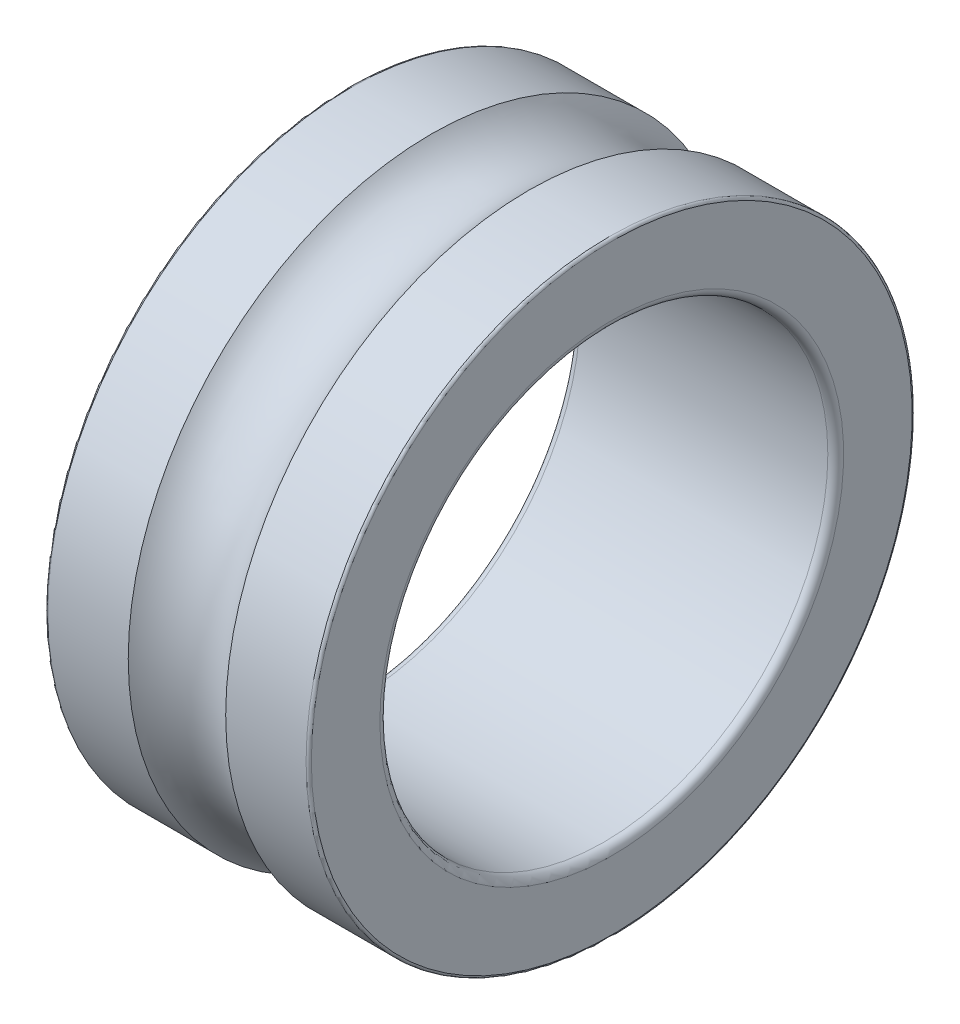
SolidWorks part; units mm, degrees
ref_plane "Plan de face" through (0, 0, 0) normal (0, 0, 1) x (1, 0, 0)
ref_plane "Plan de dessus" through (0, 0, 0) normal (0, 1, 0) x (1, 0, 0)
ref_plane "Plan de droite" through (0, 0, 0) normal (1, 0, 0) x (0, 0, -1)
ref_plane "Plan1" through (0, 0, 0) normal (0, 0, 1) x (1, 0, 0)
sketch "Esquisse1" plane through (0, 0, 0) normal (0, 0, 1) x (1, 0, 0)
  line L0 (0.3, 8.5) -> (9.7, 8.5)
  line L1 (10, 8.8) -> (10, 11.4)
  line L2 (9.9, 11.5) -> (6.8491, 11.5)
  line L3 (3.1509, 11.5) -> (0.1, 11.5)
  line L4 (0, 11.4) -> (0, 8.8)
  line L5 (100, 0) -> (-100, 0) construction
  arc A0 (0, 8.8) -> (0.3, 8.5) centre (0.3, 8.8) ccw
  arc A1 (9.7, 8.5) -> (10, 8.8) centre (9.7, 8.8) ccw
  arc A2 (10, 11.4) -> (9.9, 11.5) centre (9.9, 11.4) ccw
  arc A3 (6.8491, 11.5) -> (3.1509, 11.5) centre (5, 13) cw
  arc A4 (0.1, 11.5) -> (0, 11.4) centre (0.1, 11.4) ccw
revolve "Révolution1" add sketch "Esquisse1" angle 360 about L5
